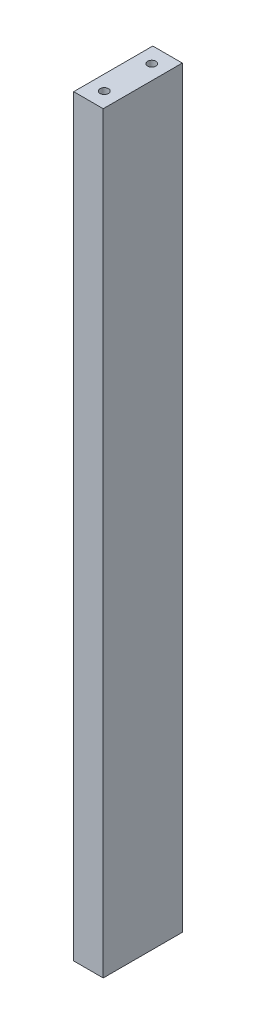
SolidWorks part; units mm, degrees
ref_plane "Front Plane" through (0, 0, 0) normal (0, 0, 1) x (1, 0, 0)
ref_plane "Top Plane" through (0, 0, 0) normal (0, 1, 0) x (1, 0, 0)
ref_plane "Right Plane" through (0, 0, 0) normal (1, 0, 0) x (0, 0, -1)
ref_plane "Back Plane" through (0, 0, -75) normal (0, 0, 1) x (1, 0, 0)
ref_plane "Bottom Plane" through (0, -714, 0) normal (0, 1, 0) x (-1, 0, 0)
ref_plane "Left Plane" through (-28, 0, 0) normal (1, 0, 0) x (0, 0, -1)
sketch "Sketch1" plane through (0, -714, 0) normal (0, 1, 0) x (-1, 0, 0)
  line L0 (55, -75) -> (-55, -75) construction
  line L1 (0, -75) -> (28, -75)
  line L2 (0, -75) -> (0, 0)
  line L3 (0, 0) -> (28, 0)
  line L4 (28, -75) -> (28, 0)
  line L5 (0, 55) -> (0, -55) construction
  line L6 (28, 55) -> (28, -55) construction
  line L7 (55, 0) -> (-55, 0) construction
extrude "Left Hand End" add sketch "Sketch1" along normal up to surface (714 mm away) up to plane "Top Plane"
sketch "Sketch2" plane through (0, 0, 0) normal (0, 1, 0) x (1, 0, 0)
  line L0 (-28, 0) -> (0, 0) construction
  line L1 (0, 75) -> (-28, 75) construction
  line L2 (-14, 0) -> (-14, 75) construction
  circle A0 centre (-14, 15) radius 4
  circle A1 centre (-14, 60) radius 4
  dimension "D3" = 8
  dimension "D1" = 15
  dimension "D2" = 15
extrude "Extrude1" cut sketch "Sketch2" against normal blind 10
sketch "Sketch3" plane through (0, -714, 0) normal (0, 1, 0) x (-1, 0, 0)
  circle A0 centre (14, -60) radius 4 construction
  circle A1 centre (14, -15) radius 4 construction
  circle A2 centre (14, -60) radius 4
  circle A3 centre (14, -15) radius 4
extrude "Extrude2" cut sketch "Sketch3" along normal blind 10
